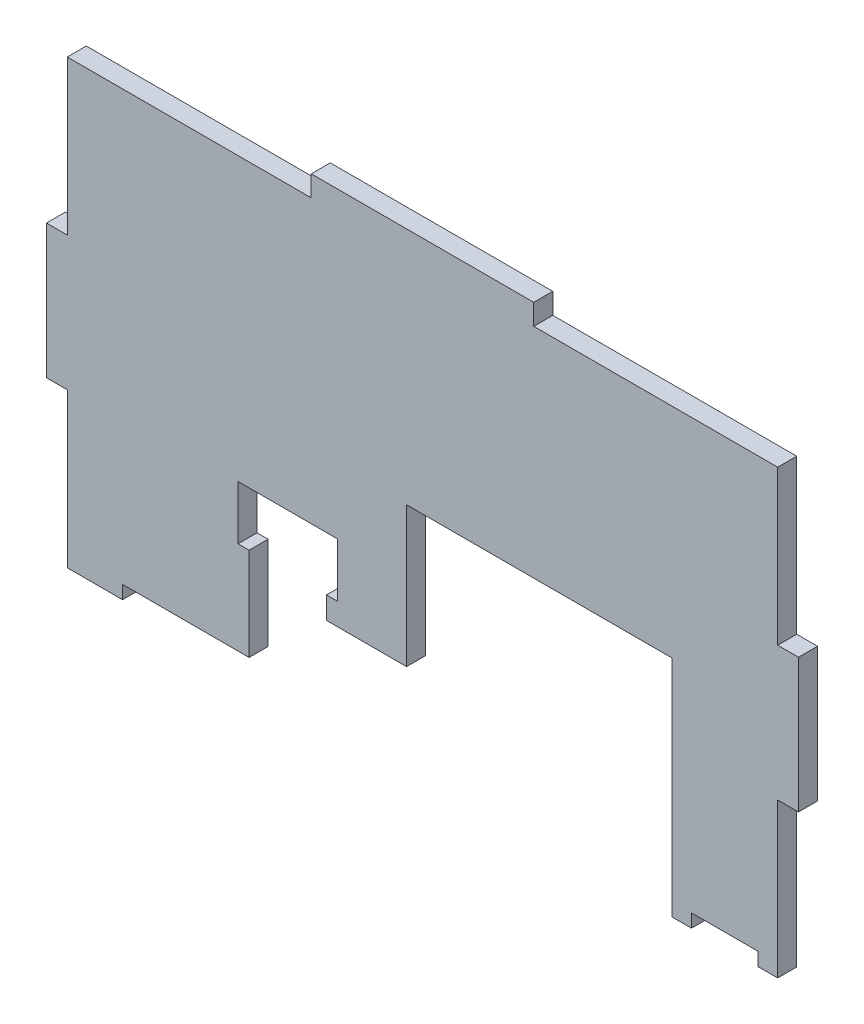
SolidWorks part; units mm, degrees
ref_plane "Front Plane" through (0, 0, 0) normal (0, 0, 1) x (1, 0, 0)
ref_plane "Top Plane" through (0, 0, 0) normal (0, 1, 0) x (1, 0, 0)
ref_plane "Right Plane" through (0, 0, 0) normal (1, 0, 0) x (0, 0, -1)
sketch "Sketch1" plane through (0, 0, 0) normal (0, 0, 1) x (1, 0, 0)
  line L1 (0, 0) -> (12.5, 0)
  line L2 (0, 0) -> (0, 34.85)
  line L3 (0, 100) -> (55.15, 100)
  line L4 (160.6, 0) -> (160.6, 34.85)
  line L5 (78.4, 0) -> (136.7, 0)
  line L6 (76.7, 19) -> (76.7, 50.7)
  line L7 (76.7, 50.7) -> (136.7, 50.7)
  line L8 (136.7, 0) -> (136.7, 50.7)
  line L10 (38.6, 24) -> (38.6, 36.2)
  line L11 (38.6, 36.2) -> (61.1, 36.2)
  line L12 (61.1, 24) -> (61.1, 36.2)
  line L16 (0, 65.15) -> (0, 100)
  line L24 (160.6, 34.85) -> (165.3, 34.85)
  line L28 (55, 30.15) -> (94.85, 30.15) construction
  line L29 (156.1, 0) -> (160.6, 0)
  line L31 (141.1, 0) -> (141.1, 3)
  line L32 (141.1, 3) -> (156.1, 3)
  line L33 (156.1, 0) -> (156.1, 3)
  line L34 (41.1, 0) -> (141.1, 0)
  line L36 (12.5, 0) -> (12.5, 3)
  line L37 (12.5, 3) -> (27.5, 3)
  line L39 (61.1, 24) -> (58.6, 24)
  line L40 (58.6, 24) -> (58.6, 19)
  line L41 (38.6, 24) -> (41.1, 24)
  line L42 (41.1, 24) -> (41.1, 0)
  line L43 (55, 30.15) -> (85.5269, 55.7651) construction
  line L44 (55, 30.15) -> (55, 70) construction
  line L50 (160.6, 65.15) -> (165.3, 65.15)
  line L51 (165.3, 34.85) -> (165.3, 65.15)
  line L56 (105.45, 100) -> (160.6, 100)
  line L57 (-4.7, 34.85) -> (0, 34.85)
  line L58 (76.7, 19) -> (61.1, 19)
  line L59 (160.6, 65.15) -> (160.6, 100)
  line L60 (61.1, 19) -> (58.6, 19)
  line L62 (55.15, 100) -> (55.15, 104.7)
  line L63 (55.15, 104.7) -> (105.45, 104.7)
  line L64 (105.45, 100) -> (105.45, 104.7)
  line L65 (-4.7, 34.85) -> (-4.7, 65.15)
  line L66 (-4.7, 65.15) -> (0, 65.15)
  line L68 (27.5, 3) -> (41.1, 3)
  line L69 (41.1, 0) -> (65.9, 0)
  arc A2 (85.5269, 55.7651) -> (39.3257, 66.788) centre (55, 30.15) ccw construction
  circle A3 centre (55, 70) radius 16 construction
  circle A4 centre (85.5269, 55.7651) radius 16 construction
  circle A6 centre (55, 70) radius 20 construction
  point P13 (165.3, 50)
  point P17 (55, 30.15)
  point P20 (20, 3)
  point P22 (94.85, 30.15)
  point P34 (55, 30.1)
  point P40 (80.3, 104.7)
  point P45 (85.5269, 55.7651)
  point P49 (148.6, 3)
  point P57 (-4.7, 50)
  dimension "D19" = 32
  dimension "D1" = 100
  dimension "D2" = 160.6
  dimension "D3" = 50.7
  dimension "D4" = 60
  dimension "D5" = 36.2
  dimension "D6" = 22.5
  dimension "D7" = 23.9
  dimension "D8" = 15
  dimension "D10" = 12
  dimension "D11" = 3
  dimension "D12" = 15
  dimension "D14" = 20
  dimension "D15" = 12.2
  dimension "D16" = 39.85
  dimension "D17" = 2.5
  dimension "D18" = 2.5
  dimension "D20" = 40
  dimension "D21" = 4.7
  dimension "D22" = 50
  dimension "D23" = 50
  dimension "D24" = 80.3
  dimension "D25" = 50.3
  dimension "D26" = 4.7
  dimension "D27" = 30.3
  dimension "D28" = 4.7
  dimension "D29" = 50
  dimension "D30" = 15.6
  dimension "D31" = 5
  dimension "D9" = 30.3
extrude "Boss-Extrude1" add sketch "Sketch1" along normal blind 4.3
equation "\"15ز1\"=16.5971"
